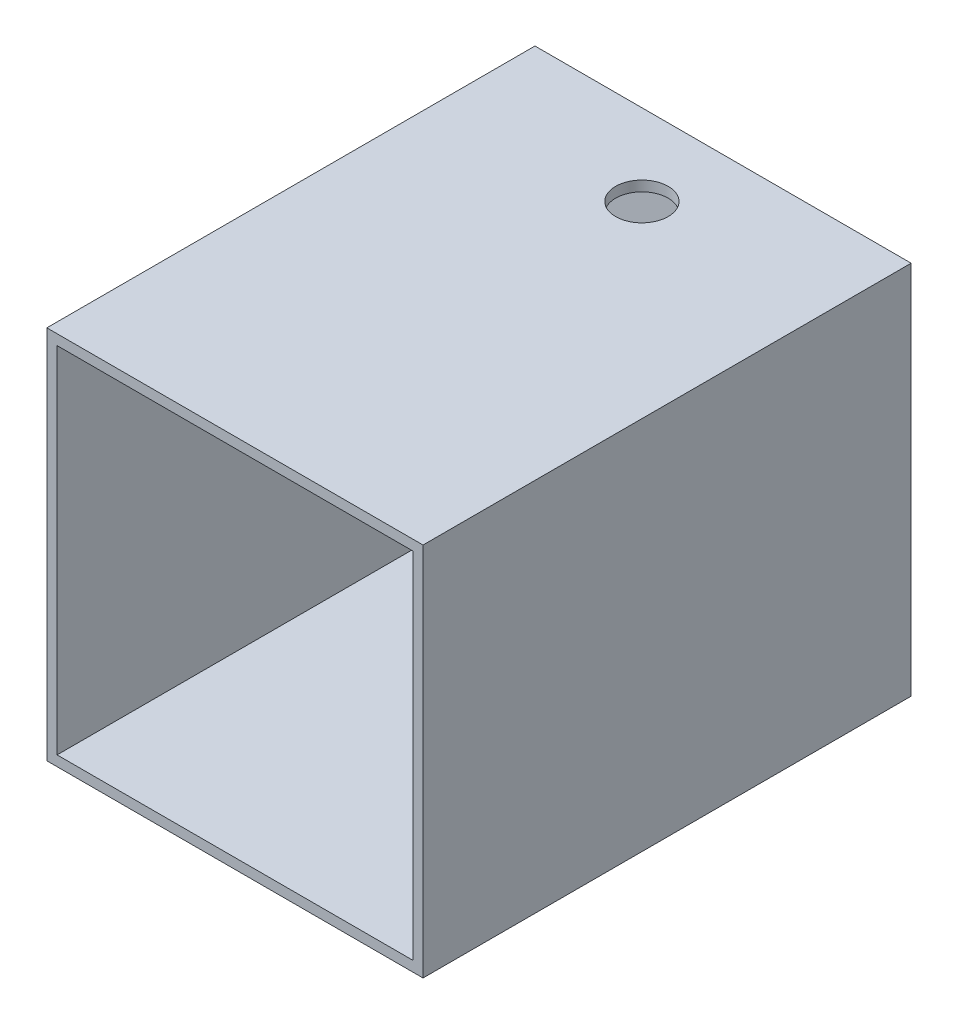
SolidWorks part; units mm, degrees
ref_plane "Alzado" through (0, 0, 0) normal (0, 0, 1) x (1, 0, 0)
ref_plane "Planta" through (0, 0, 0) normal (0, 1, 0) x (1, 0, 0)
ref_plane "Vista lateral" through (0, 0, 0) normal (1, 0, 0) x (0, 0, -1)
sketch "Croquis1" plane through (0, 0, 0) normal (0, 0, 1) x (1, 0, 0)
  line L0 (-74.5, 74.25) -> (-74.5, -74.25)
  line L1 (-78.8, 78.55) -> (78.8, 78.55)
  line L2 (-78.8, 78.55) -> (-78.8, -78.55)
  line L3 (-78.8, -78.55) -> (78.8, -78.55)
  line L4 (78.8, 78.55) -> (78.8, -78.55)
  line L5 (-78.8, 78.55) -> (78.8, -78.55) construction
  line L6 (-78.8, -78.55) -> (78.8, 78.55) construction
  line L7 (-74.5, -74.25) -> (74.5, -74.25)
  line L8 (74.5, 74.25) -> (74.5, -74.25)
  line L9 (-74.5, 74.25) -> (74.5, 74.25)
  point P0 (0, 0)
  dimension "D1" = 157.6
  dimension "D2" = 157.1
  dimension "D3" = 4.3
extrude "Saliente-Extruir1" add sketch "Croquis1" along normal blind 204.5
sketch "Croquis2" plane through (-74.5, 0, 0) normal (1, 0, 0) x (0, 0, -1)
  line L0 (-204.5, -78.55) -> (0, -78.55) construction
  line L1 (0, 78.55) -> (-4, 78.55)
  line L2 (0, 78.55) -> (0, -78.55)
  line L3 (0, -78.55) -> (-4, -78.55)
  line L4 (-4, 78.55) -> (-4, -78.55)
  dimension "D1" = 4
extrude "Saliente-Extruir2" add sketch "Croquis2" along normal up to surface (149 mm away) up to face at (74.5, 0, 102.25)
sketch "Croquis3" plane through (0, -78.55, 0) normal (0, -1, 0) x (1, 0, 0)
  line L0 (74.5, 4) -> (-74.5, 4) construction
  circle A0 centre (0, 34) radius 29.5 construction
  circle A1 centre (0, 34) radius 11
  dimension "D1" = 59
  dimension "D2" = 30
  dimension "D3" = 22
extrude "Cortar-Extruir1" cut sketch "Croquis3" against normal through all
